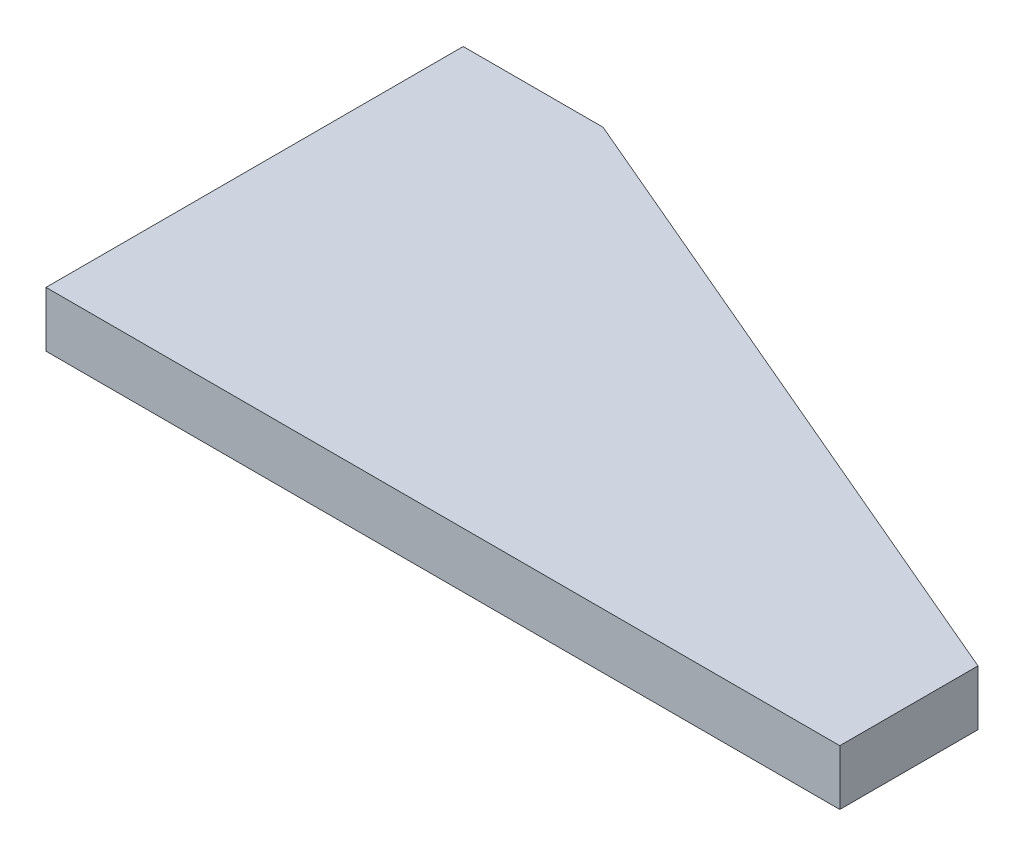
SolidWorks part; units mm, degrees
ref_plane "Спереди" through (0, 0, 0) normal (0, 0, 1) x (1, 0, 0)
ref_plane "Сверху" through (0, 0, 0) normal (0, 1, 0) x (1, 0, 0)
ref_plane "Справа" through (0, 0, 0) normal (1, 0, 0) x (0, 0, -1)
sketch "Эскиз1" plane through (0, 0, 0) normal (0, 1, 0) x (1, 0, 0)
  line L0 (10.1211, 30.187) -> (57.4341, 10)
  line L1 (0, 0) -> (57.4341, 0)
  line L2 (0, 0) -> (0, 30.187)
  line L3 (0, 30.187) -> (10.1211, 30.187)
  line L4 (57.4341, 0) -> (57.4341, 10)
  line L5 (10.1211, 10) -> (10.1211, 84.9999) construction
  line L6 (200, 10) -> (0, 10) construction
  line L7 (20, 42.9767) -> (7.6162, 42.9767) construction
extrude "Вытянуть1" add sketch "Эскиз1" along normal blind 4
